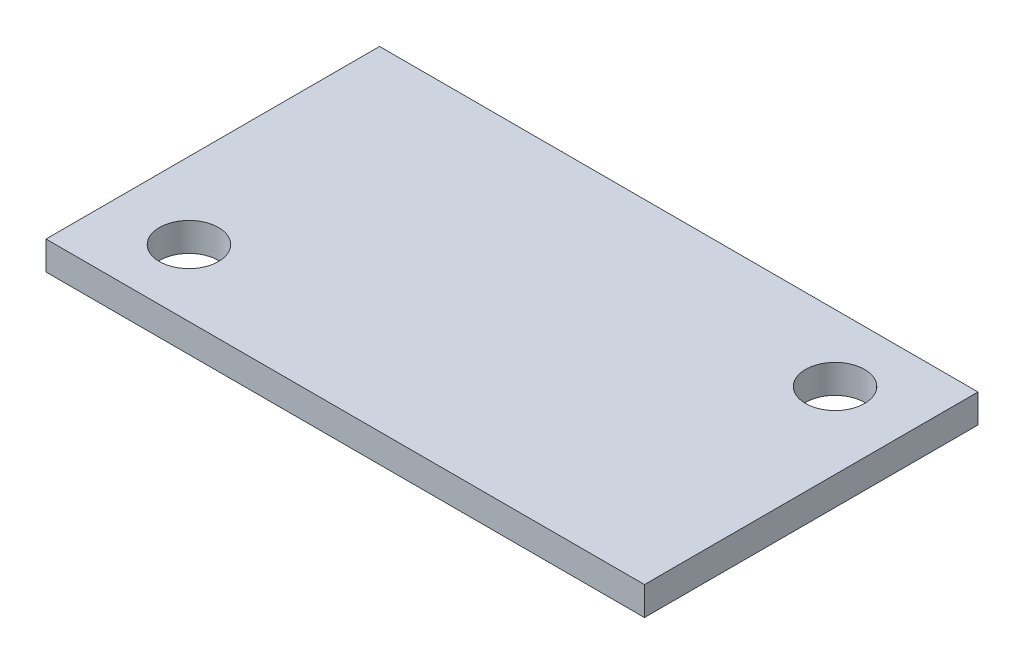
SolidWorks part; units mm, degrees
ref_plane "Płaszczyzna przednia" through (0, 0, 0) normal (0, 0, 1) x (1, 0, 0)
ref_plane "Płaszczyzna górna" through (0, 0, 0) normal (0, 1, 0) x (1, 0, 0)
ref_plane "Płaszczyzna prawa" through (0, 0, 0) normal (1, 0, 0) x (0, 0, -1)
sketch "Szkic1" plane through (0, -21.8164, 0) normal (0, -1, 0) x (1, 0, 0)
  line L0 (331.4605, -469.0288) -> (362.8605, -469.0288)
  line L1 (331.4605, -469.0288) -> (331.4605, -451.5288)
  line L2 (362.8605, -469.0288) -> (362.8605, -451.5288)
  line L3 (331.4605, -451.5288) -> (362.8605, -451.5288)
  dimension "D1" = 17.5
  dimension "D2" = 31.4
extrude "Dodanie-wyciągnięcie1" add sketch "Szkic1" along normal blind 1.5
sketch "Szkic2" plane through (0, -23.3164, 0) normal (0, -1, 0) x (1, 0, 0)
  line L0 (362.8605, -451.5288) -> (331.4605, -451.5288) construction
  line L1 (362.8605, -469.0288) -> (362.8605, -451.5288) construction
  line L2 (331.4605, -451.5288) -> (331.4605, -469.0288) construction
  line L3 (331.4605, -469.0288) -> (362.8605, -469.0288) construction
  circle A0 centre (358.8605, -465.5288) radius 1.55
  circle A1 centre (335.4605, -455.0288) radius 1.55
  dimension "D1" = 3.1
  dimension "D2" = 3.1
  dimension "D3" = 3.5
  dimension "D4" = 3.5
  dimension "D5" = 4
  dimension "D6" = 4
extrude "Wytnij-wyciągnięcie1" cut sketch "Szkic2" against normal blind 1.5
sketch "Szkic3" plane through (0, -23.3164, 0) normal (0, -1, 0) x (1, 0, 0)
  line L0 (347.2105, -457.8288) -> (350.1105, -457.8288)
  line L1 (347.2105, -457.8288) -> (347.2105, -456.2288)
  line L2 (350.1105, -457.8288) -> (350.1105, -456.2288)
  line L3 (347.2105, -456.2288) -> (350.1105, -456.2288)
  line L5 (362.8605, -451.5288) -> (331.4605, -451.5288) construction
  circle A0 centre (335.4605, -455.0288) radius 1.55 construction
  dimension "D1" = 2.9
  dimension "D2" = 1.6
  dimension "D3" = 4.7
  dimension "D4" = 11.75
extrude "Dodanie-wyciągnięcie2" add sketch "Szkic3" along normal blind 1.8
sketch "Szkic4" plane through (0, -23.3164, 0) normal (0, -1, 0) x (1, 0, 0)
  line L0 (337.4605, -459.7788) -> (337.4605, -467.2788)
  line L1 (337.4605, -459.7788) -> (340.4605, -459.7788)
  line L2 (337.4605, -467.2788) -> (340.4605, -467.2788)
  line L3 (340.4605, -459.7788) -> (340.4605, -467.2788)
  line L4 (331.4605, -451.5288) -> (331.4605, -469.0288) construction
  line L5 (331.4605, -469.0288) -> (362.8605, -469.0288) construction
  point P0 (337.4605, -463.5288)
  dimension "D1" = 7.5
  dimension "D2" = 3
  dimension "D3" = 1.75
  dimension "D4" = 6
extrude "Dodanie-wyciągnięcie3" add sketch "Szkic4" along normal blind 2.5
sketch "Szkic6" plane through (337.4605, 0, 0) normal (-1, 0, 0) x (0, 0, 1)
  line L0 (-460.5288, -24.0664) -> (-461.5288, -24.0664)
  line L1 (-460.5288, -24.0664) -> (-460.5288, -25.0664)
  line L2 (-461.5288, -24.0664) -> (-461.5288, -25.0664)
  line L3 (-460.5288, -25.0664) -> (-461.5288, -25.0664)
  line L4 (-459.7788, -25.8164) -> (-459.7788, -23.3164) construction
  line L5 (-459.7788, -23.3164) -> (-467.2788, -23.3164) construction
  dimension "D1" = 1
  dimension "D2" = 1
  dimension "D3" = 0.75
  dimension "D4" = 0.75
extrude "Dodanie-wyciągnięcie5" add sketch "Szkic6" along normal blind 5.8
pattern_linear "Szyk liniowy3" count 3 spacing 2.5 along (0, 0, -1) of "Dodanie-wyciągnięcie5"
sketch "Szkic7" plane through (0, -25.1164, 0) normal (0, -1, 0) x (1, 0, 0)
  line L0 (348.6605, -457.8288) -> (348.6605, -456.2288)
  line L1 (347.2105, -457.8288) -> (350.1105, -457.8288) construction
  line L2 (350.1105, -456.2288) -> (347.2105, -456.2288) construction
  circle A0 centre (348.6605, -457.0288) radius 0.46
  point P6 (348.6605, -457.0288)
equation "\"tolerancja_wpusy\"=0.2"
equation "\"dlugosc_wpustu_duzy\"=20"
equation "\"srednica_otworu_M3\"=3.1"
equation "\"szerokosc_nogi_T\"=3.1"
equation "\"dlugosc_T_30\"=11"
equation "\"grubosc_na_nakretke_kwadrat\"=2"
equation "\"szerokosc_na_nakretke_kwadrat\"=5.85"
equation "\"wyokosc_nadstawki_T\"=0.5"
equation "\"dlugosc_T_20_6\"=14"
equation "\"D1@Szkic2\"=\"srednica_otworu_M3\""
equation "\"D2@Szkic2\"=\"srednica_otworu_M3\""
